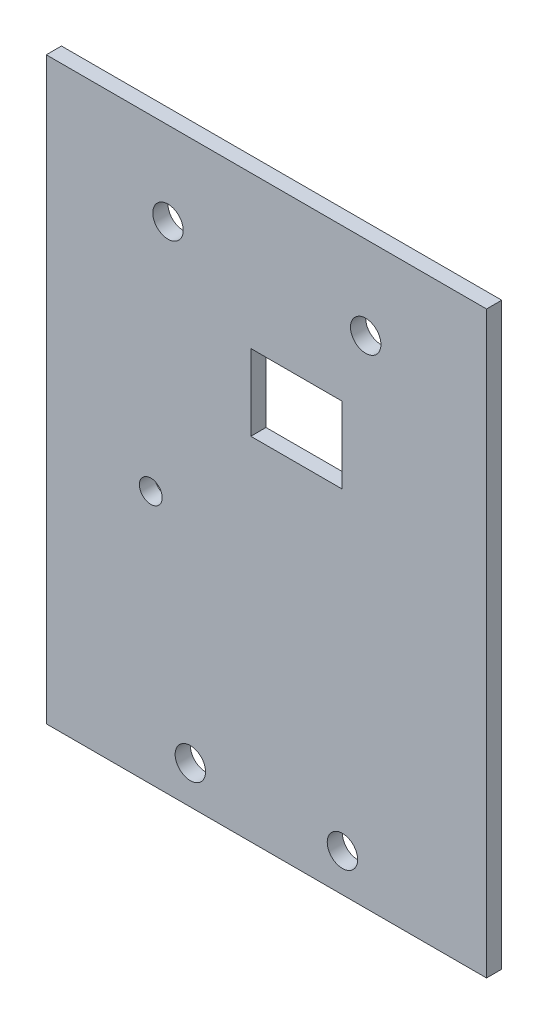
SolidWorks part; units mm, degrees
ref_plane "Front Plane" through (0, 0, 0) normal (0, 0, 1) x (1, 0, 0)
ref_plane "Top Plane" through (0, 0, 0) normal (0, 1, 0) x (1, 0, 0)
ref_plane "Right Plane" through (0, 0, 0) normal (1, 0, 0) x (0, 0, -1)
sketch "Sketch1" plane through (0, 0, 0) normal (0, 0, 1) x (1, 0, 0)
  line L1 (-35.5404, 29.2034) -> (22.3596, 29.2034)
  line L2 (-35.5404, 29.2034) -> (-35.5404, -46.9966)
  line L3 (-35.5404, -46.9966) -> (22.3596, -46.9966)
  line L4 (22.3596, 29.2034) -> (22.3596, -46.9966)
  dimension "D1" = 57.9
  dimension "D2" = 76.2
extrude "Boss-Extrude1" add sketch "Sketch1" along normal blind 2
sketch "Sketch2" plane through (0, 0, 0) normal (0, 0, -1) x (-1, 0, 0)
  line L0 (6.5904, 29.2034) -> (6.5904, 20.2034)
  line L1 (-22.3596, 29.2034) -> (35.5404, 29.2034) construction
  line L2 (26.9623, 24.7034) -> (-15.5564, 24.7034) construction
  line L3 (-6.4096, 24.7034) -> (19.5904, 24.7034)
  line L4 (19.5904, 24.7034) -> (19.5904, 14.2034)
  line L5 (19.5904, 14.2034) -> (-6.4096, 14.2034)
  line L6 (-3.3596, 4.2034) -> (8.6404, 4.2034)
  line L7 (-22.3596, 29.2034) -> (2.6404, 29.2034)
  line L8 (-22.3596, 29.2034) -> (-22.3596, 4.2034)
  line L9 (-22.3596, 4.2034) -> (2.6404, 4.2034)
  line L10 (2.6404, 29.2034) -> (2.6404, 4.2034)
  line L11 (2.6404, 4.2034) -> (2.6404, 9.2034)
  line L12 (12.201, -46.9966) -> (12.201, -41.9966)
  line L13 (8.6404, 9.2034) -> (-3.3596, 9.2034)
  line L14 (8.6404, 9.2034) -> (8.6404, -0.7966)
  line L15 (8.6404, -0.7966) -> (-3.3596, -0.7966)
  line L16 (-3.3596, 9.2034) -> (-3.3596, -0.7966)
  line L17 (35.5404, -46.9966) -> (-22.3596, -46.9966) construction
  line L18 (35.5404, -41.9966) -> (-22.3596, -41.9966) construction
  line L19 (35.5404, 29.2034) -> (35.5404, -46.9966) construction
  line L20 (-22.3596, -46.9966) -> (-22.3596, 29.2034) construction
  line L21 (35.5404, -41.9966) -> (-22.3596, -41.9966)
  line L22 (-3.4096, -41.9966) -> (16.5904, -41.9966)
  line L24 (35.5404, 29.2034) -> (21.7904, 29.2034)
  line L25 (35.5404, 29.2034) -> (35.5404, -13.6266)
  line L26 (35.5404, -13.6266) -> (21.7904, -13.6266)
  line L27 (21.7904, 29.2034) -> (21.7904, -13.6266)
  circle A0 centre (19.5904, 14.2034) radius 2
  circle A1 centre (-6.4096, 14.2034) radius 2
  circle A2 centre (16.5904, -41.9966) radius 2
  circle A3 centre (-3.4096, -41.9966) radius 2
  circle A4 centre (21.7904, -13.6266) radius 1.5
  point P9 (6.5904, 24.7034)
  point P21 (2.6404, 4.2034)
  point P39 (6.5904, -41.9966)
  dimension "D3" = 4
  dimension "D4" = 4
  dimension "D11" = 4
  dimension "D12" = 4
  dimension "D15" = 3
  dimension "D1" = 9
  dimension "D2" = 10.5
  dimension "D5" = 25
  dimension "D6" = 6
  dimension "D7" = 5
  dimension "D8" = 10
  dimension "D9" = 12
  dimension "D10" = 5
  dimension "D13" = 42.83
  dimension "D14" = 13.75
extrude "Cut-Extrude1" cut sketch "Sketch2" against normal up to surface (2 mm away)
sketch "Sketch4" plane through (0, 0, 0) normal (0, 0, -1) x (-1, 0, 0)
  line L0 (-3.3596, 9.2034) -> (-3.3596, 18.3231)
  line L1 (6.5904, 29.2034) -> (6.5904, 14.2034)
  line L2 (-22.3596, 29.2034) -> (35.5404, 29.2034) construction
  line L3 (19.5904, 16.1606) -> (6.5904, 16.1606)
  line L5 (-13.6502, 24.4874) -> (30.1504, 24.4874)
  line L6 (-13.6502, 24.4874) -> (-13.6502, 9.2034)
  line L7 (-13.6502, 9.2034) -> (30.1504, 9.2034)
  line L8 (30.1504, 24.4874) -> (30.1504, 9.2034)
  circle A0 centre (-6.4096, 14.2034) radius 2
  circle A1 centre (19.5904, 14.2034) radius 1.9572
extrude "Boss-Extrude5" add sketch "Sketch4" against normal up to surface (2 mm away)
sketch "Sketch8" plane through (0, 0, 0) normal (0, 0, -1) x (-1, 0, 0)
  line L1 (-22.3596, 29.2034) -> (35.5404, 29.2034)
  line L2 (-22.3596, 29.2034) -> (-22.3596, -46.9966)
  line L3 (-22.3596, -46.9966) -> (35.5404, -46.9966)
  line L4 (35.5404, 29.2034) -> (35.5404, -46.9966)
  line L8 (35.5404, -46.9966) -> (35.5404, 29.2034)
  line L9 (-22.3596, -46.9966) -> (35.5404, -46.9966)
  line L10 (-22.3596, 29.2034) -> (-22.3596, -46.9966)
  line L11 (35.5404, 29.2034) -> (-22.3596, 29.2034)
  line L12 (35.5404, -46.9966) -> (35.5404, 29.2034)
  line L13 (-22.3596, -46.9966) -> (35.5404, -46.9966)
  line L14 (-22.3596, 29.2034) -> (-22.3596, -46.9966)
  line L15 (35.5404, 29.2034) -> (-22.3596, 29.2034)
  line M13 (-3.3596, 9.2034) -> (8.6404, 9.2034)
  line M14 (8.6404, 9.2034) -> (8.6404, -0.7966)
  line M15 (8.6404, -0.7966) -> (-3.3596, -0.7966)
  line M16 (-3.3596, -0.7966) -> (-3.3596, 9.2034)
  line M17 (35.5404, -46.9966) -> (35.5404, 29.2034)
  line M18 (35.5404, 29.2034) -> (-22.3596, 29.2034)
  line M19 (-22.3596, 29.2034) -> (-22.3596, -46.9966)
  line M20 (-22.3596, -46.9966) -> (35.5404, -46.9966)
  circle M21 centre (16.5904, -41.9966) radius 2
  circle M22 centre (-3.4096, -41.9966) radius 2
  circle M23 centre (21.7904, -13.6266) radius 1.5
  circle M24 centre (19.5904, 14.2034) radius 2
  dimension "D1" = 0
extrude "Boss-Extrude6" add sketch "Sketch8" along normal blind 10 contours M20 M17 M18 M19 M21 M23 M24 M22 M16 M13 M14 M15 | M24
sketch "Sketch9" plane through (0, 0, -10) normal (0, 0, -1) x (-1, 0, 0)
  line L0 (6.5318, 9.2034) -> (6.5318, 18.2034)
  line L1 (-3.3596, 9.2034) -> (8.6404, 9.2034) construction
  line L2 (6.5904, 29.2034) -> (6.5318, 18.2034)
  line L3 (35.5404, 29.2034) -> (-22.3596, 29.2034) construction
  line L4 (-6.4682, 18.2034) -> (19.5318, 18.2034)
  circle A0 centre (-6.4682, 18.2034) radius 2
  circle A1 centre (19.5318, 18.2034) radius 2
  point P10 (6.5318, 18.2034)
  dimension "D3" = 4
  dimension "D4" = 4
  dimension "D1" = 9
  dimension "D2" = 13
extrude "Cut-Extrude6" cut sketch "Sketch9" against normal blind 10
sketch "Sketch10" plane through (0, 0, 2) normal (0, 0, 1) x (1, 0, 0)
  line L1 (-35.5404, 29.2034) -> (22.3596, 29.2034)
  line L2 (-35.5404, 29.2034) -> (-35.5404, -46.9966)
  line L3 (-35.5404, -46.9966) -> (22.3596, -46.9966)
  line L4 (22.3596, 29.2034) -> (22.3596, -46.9966)
extrude "Cut-Extrude7" cut sketch "Sketch10" against normal blind 10
